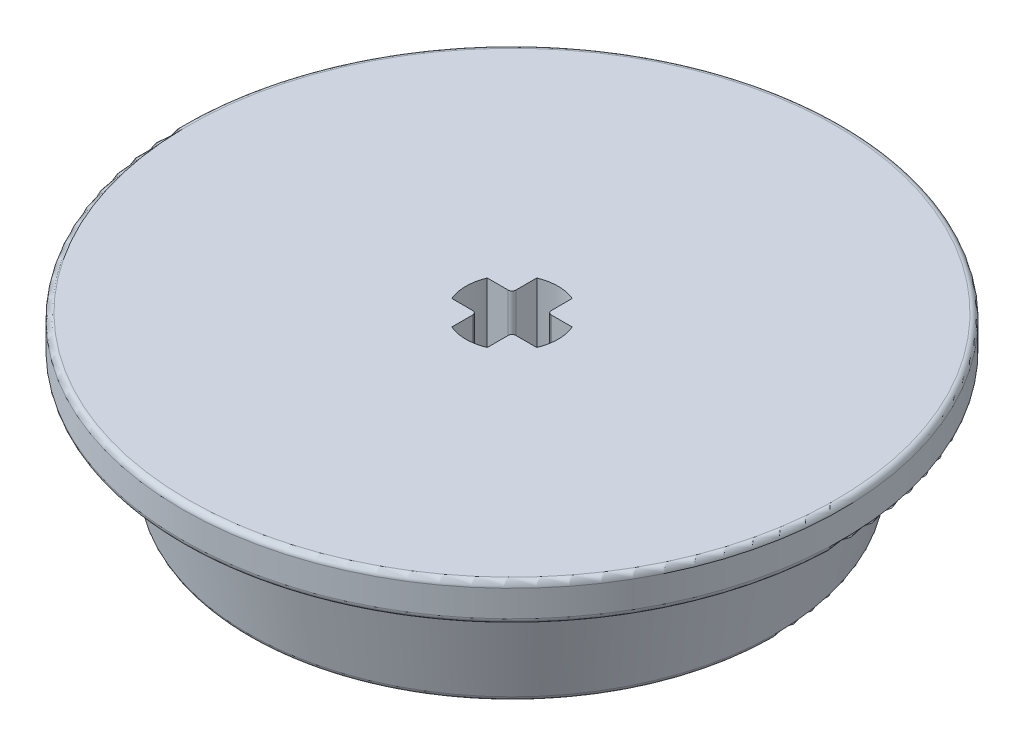
SolidWorks part; units mm, degrees
ref_plane "Front Plane" through (0, 0, 0) normal (0, 0, 1) x (1, 0, 0)
ref_plane "Top Plane" through (0, 0, 0) normal (0, 1, 0) x (1, 0, 0)
ref_plane "Right Plane" through (0, 0, 0) normal (1, 0, 0) x (0, 0, -1)
sketch "Sketch1" plane through (0, 0, 0) normal (0, 1, 0) x (1, 0, 0)
  line L2 (0, 0) -> (0, 47.5777) construction
  line L3 (0, 0) -> (50000, 0) construction
  line L6 (-0.89, 0.89) -> (0, 0) construction
  line L7 (0, 0) -> (0.89, 0.89) construction
  line L12 (2.39, 0) -> (2.39, 3.5727) construction
  line L13 (0, 2.39) -> (50000, 2.39) construction
  line L14 (-2.39, 0.4111) -> (-2.39, -49999.5889) construction
  line L15 (0.2318, -2.39) -> (-49999.7682, -2.39) construction
  line L16 (0, 0) -> (-0.89, -0.89) construction
  line L17 (0, 0) -> (0.89, -0.89) construction
  line L18 (-0.94, 0.94) -> (-2.2517, 0.94)
  line L19 (-2.2517, -0.94) -> (-0.94, -0.94)
  line L20 (-0.94, -0.94) -> (-0.94, -2.2517)
  line L21 (0.94, -2.2517) -> (0.94, -0.94)
  line L22 (0.94, -0.94) -> (2.2517, -0.94)
  line L23 (0.94, 0.94) -> (2.2517, 0.94)
  line L24 (0.94, 2.2517) -> (0.94, 0.94)
  line L25 (-0.94, 2.2517) -> (-0.94, 0.94)
  arc A4 (-2.2517, 0.94) -> (-2.2517, -0.94) centre (0, 0) ccw
  arc A5 (-0.94, -2.2517) -> (0.94, -2.2517) centre (0, 0) ccw
  arc A6 (2.2517, 0.94) -> (2.2517, -0.94) centre (0, 0) cw
  arc A7 (-0.94, 2.2517) -> (0.94, 2.2517) centre (0, 0) cw
  point P15 (0, 2.39)
  point P24 (2.39, 0)
  point P29 (-2.39, 0)
  point P30 (0, -2.39)
  line B0 (-0.89, 2.2181) -> (-0.89, 0.89) construction
  line B1 (-0.89, 0.89) -> (-2.2181, 0.89) construction
  line B2 (0.89, 2.2181) -> (0.89, 0.89) construction
  line B3 (0.89, 0.89) -> (2.2181, 0.89) construction
  line B4 (-2.2181, -0.89) -> (-0.89, -0.89) construction
  line B5 (-0.89, -0.89) -> (-0.89, -2.2181) construction
  line B6 (0.89, -2.2181) -> (0.89, -0.89) construction
  line B7 (0.89, -0.89) -> (2.2181, -0.89) construction
  arc B8 (-0.89, 2.2181) -> (0.89, 2.2181) centre (0, 0) cw construction
  arc B9 (-2.2181, 0.89) -> (-2.2181, -0.89) centre (0, 0) ccw construction
  arc B10 (2.2181, 0.89) -> (2.2181, -0.89) centre (0, 0) cw construction
  arc B11 (-0.89, -2.2181) -> (0.89, -2.2181) centre (0, 0) ccw construction
  dimension "D1" = 45
  dimension "D2" = 45
  dimension "D3" = 4.78
  dimension "D4" = 45
  dimension "D5" = 4.78
  dimension "D6" = 1.5
sketch_block_instance "Lego Axle - Unfilleted-1"
sketch_block "Lego Axle - Unfilleted" parameters "D1"=10.5762, "D2"=12.3972, "D3"=62.5785, "D4"=1.2287, "D5"=12.9019, "D6"=1.0841, "D7"=0.05
sketch "Sketch2" plane through (0, 0, 0) normal (0, 0, 1) x (1, 0, 0)
  line L0 (0, 0) -> (17.4605, 0)
  line L1 (200000.2318, 0) -> (-249999.7682, 0) construction
  line L2 (17.4605, 0) -> (17.4605, -2)
  line L3 (17.4605, -2) -> (15, -2)
  line L4 (15, -2) -> (13.9155, -8)
  line L5 (13.9155, -8) -> (0, -8)
  line L6 (0, -8) -> (0, 0)
  line L7 (0, 0) -> (0, 50000) construction
  dimension "D1" = 30
  dimension "D2" = 27.831
  dimension "D3" = 8
  dimension "D4" = 2
revolve "Revolve1" add sketch "Sketch2" angle 360 about L7
extrude "Cut-Extrude1" cut sketch "Sketch1" against normal through all
fillet "Fillet1" radius 0.2 4 edges at (-0.94, -4, 0.94) (0.94, -4, 0.94) (0.94, -4, -0.94) (-0.94, -4, -0.94)
fillet "Fillet2" radius 0.3 4 edges at (0, -8, -13.9155) (0, 0, -17.4605) (0, -2, -15) (0, -2, -17.4605)
equation "\"D2@Sketch2\"=0.9277*\"D1@Sketch2\""
